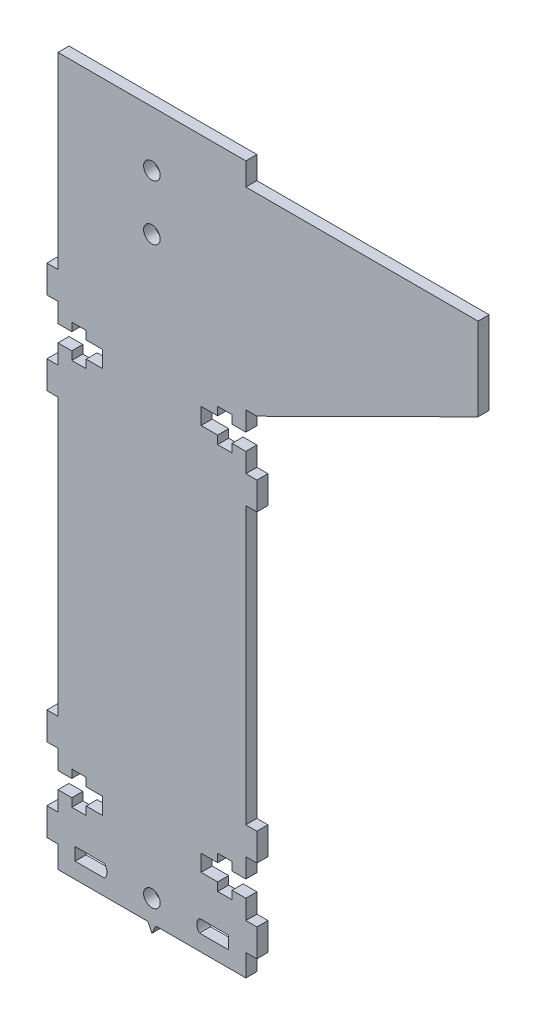
SolidWorks part; units mm, degrees
ref_plane "前视基准面" through (0, 0, 0) normal (0, 0, 1) x (1, 0, 0)
ref_plane "上视基准面" through (0, 0, 0) normal (0, 1, 0) x (1, 0, 0)
ref_plane "右视基准面" through (0, 0, 0) normal (1, 0, 0) x (0, 0, -1)
sketch "草图1" plane through (0, 0, 0) normal (0, 0, 1) x (1, 0, 0)
  line L35 (16.9939, 15.9) -> (16.9939, 20)
  line L36 (58.9939, 15.9) -> (16.9939, 15.9)
  line L37 (58.9939, 0.9) -> (58.9939, 15.9)
  line L40 (18.9939, -34) -> (16.9939, -34)
  line L41 (18.9939, -29) -> (16.9939, -29)
  line L42 (18.9939, -34) -> (18.9939, -29)
  line L47 (16.9939, -22.5) -> (16.9939, -19)
  line L64 (0, -108) -> (0, -109.5)
  line L77 (-13.9, -102.85) -> (-8.6, -102.85)
  line L78 (-13.9, -102.85) -> (-13.9, -105.15)
  line L79 (-13.9, -105.15) -> (-8.6, -105.15)
  line L94 (0, -109.5) -> (0.7212, -108)
  line L95 (0.7212, -108) -> (16.9939, -108)
  line L96 (-0.7212, -108) -> (-16.9939, -108)
  line L97 (0, -109.5) -> (-0.7212, -108)
  line L124 (16.9939, -25.5) -> (16.9939, -29)
  line L126 (14.4939, -25.5) -> (16.9939, -25.5)
  line L127 (14.4939, -21) -> (11.8939, -21)
  line L128 (11.8939, -21) -> (11.8939, -22.5)
  line L129 (11.8939, -22.5) -> (8.8939, -22.5)
  line L130 (11.8939, -25.5) -> (8.8939, -25.5)
  line L131 (11.8939, -27) -> (11.8939, -25.5)
  line L132 (14.4939, -27) -> (11.8939, -27)
  line L133 (16.9939, -22.5) -> (14.4939, -22.5)
  line L134 (14.4939, -22.5) -> (14.4939, -21)
  line L135 (8.8939, -22.5) -> (8.8939, -25.5)
  line L136 (14.4939, -25.5) -> (14.4939, -27)
  line L138 (-18.9939, -104) -> (-18.9939, -99)
  line L139 (-18.9939, -99) -> (-16.9939, -99)
  line L140 (-18.9939, -104) -> (-16.9939, -104)
  line L141 (-14.4939, -95.5) -> (-14.4939, -97)
  line L142 (-8.8939, -92.5) -> (-8.8939, -95.5)
  line L143 (-14.4939, -92.5) -> (-14.4939, -91)
  line L144 (-16.9939, -92.5) -> (-14.4939, -92.5)
  line L145 (-14.4939, -97) -> (-11.8939, -97)
  line L146 (-11.8939, -97) -> (-11.8939, -95.5)
  line L147 (-11.8939, -95.5) -> (-8.8939, -95.5)
  line L148 (-11.8939, -92.5) -> (-8.8939, -92.5)
  line L149 (-11.8939, -91) -> (-11.8939, -92.5)
  line L150 (-14.4939, -91) -> (-11.8939, -91)
  line L151 (-14.4939, -95.5) -> (-16.9939, -95.5)
  line L152 (-16.9939, -89) -> (-16.9939, -92.5)
  line L153 (-16.9939, -95.5) -> (-16.9939, -99)
  line L154 (-16.9939, -89) -> (-18.9939, -89)
  line L155 (-18.9939, -89) -> (-18.9939, -84)
  line L156 (-18.9939, -84) -> (-16.9939, -84)
  line L158 (-16.9939, -104) -> (-16.9939, -108)
  line L179 (-14.4939, -25.5) -> (-14.4939, -27)
  line L180 (-8.8939, -22.5) -> (-8.8939, -25.5)
  line L181 (-14.4939, -22.5) -> (-14.4939, -21)
  line L182 (-16.9939, -22.5) -> (-14.4939, -22.5)
  line L183 (-14.4939, -27) -> (-11.8939, -27)
  line L184 (-11.8939, -27) -> (-11.8939, -25.5)
  line L185 (-11.8939, -25.5) -> (-8.8939, -25.5)
  line L186 (-11.8939, -22.5) -> (-8.8939, -22.5)
  line L187 (-11.8939, -21) -> (-11.8939, -22.5)
  line L188 (-14.4939, -21) -> (-11.8939, -21)
  line L189 (-14.4939, -25.5) -> (-16.9939, -25.5)
  line L190 (-16.9939, -25.5) -> (-16.9939, -29)
  line L191 (-16.9939, -22.5) -> (-16.9939, -19)
  line L192 (-18.9939, -34) -> (-18.9939, -29)
  line L193 (-18.9939, -29) -> (-16.9939, -29)
  line L194 (-18.9939, -34) -> (-16.9939, -34)
  line L195 (-16.9939, -34) -> (-16.9939, -84)
  line L199 (-18.9939, -19) -> (-16.9939, -19)
  line L200 (-16.9939, 15.9) -> (-16.9939, 20)
  line L201 (-16.9939, 20) -> (16.9939, 20)
  line L207 (16.9939, -84) -> (16.9939, -34)
  line L210 (-18.9939, -19) -> (-18.9939, -14)
  line L211 (-18.9939, -14) -> (-16.9939, -14)
  line L212 (-16.9939, -14) -> (-16.9939, 15.9)
  line L213 (16.9939, -19) -> (18.9939, -19)
  line L222 (0, -104) -> (0, -98.3813) construction
  line L223 (16.9939, -104) -> (16.9939, -108)
  line L224 (18.9939, -84) -> (16.9939, -84)
  line L225 (18.9939, -89) -> (18.9939, -84)
  line L226 (16.9939, -89) -> (18.9939, -89)
  line L227 (16.9939, -95.5) -> (16.9939, -99)
  line L228 (16.9939, -89) -> (16.9939, -92.5)
  line L229 (14.4939, -95.5) -> (16.9939, -95.5)
  line L230 (14.4939, -91) -> (11.8939, -91)
  line L231 (11.8939, -91) -> (11.8939, -92.5)
  line L232 (11.8939, -92.5) -> (8.8939, -92.5)
  line L233 (11.8939, -95.5) -> (8.8939, -95.5)
  line L234 (11.8939, -97) -> (11.8939, -95.5)
  line L235 (14.4939, -97) -> (11.8939, -97)
  line L236 (16.9939, -92.5) -> (14.4939, -92.5)
  line L237 (14.4939, -92.5) -> (14.4939, -91)
  line L238 (8.8939, -92.5) -> (8.8939, -95.5)
  line L239 (14.4939, -95.5) -> (14.4939, -97)
  line L240 (18.9939, -104) -> (16.9939, -104)
  line L241 (18.9939, -99) -> (16.9939, -99)
  line L242 (18.9939, -104) -> (18.9939, -99)
  line L243 (13.9, -105.15) -> (8.6, -105.15)
  line L244 (13.9, -102.85) -> (13.9, -105.15)
  line L245 (13.9, -102.85) -> (8.6, -102.85)
  line L246 (18.9939, -19) -> (58.9939, 0.9)
  circle A4 centre (0, -104) radius 1.5
  circle A6 centre (0, 0) radius 1.5
  circle A7 centre (0, 10) radius 1.5
  arc A8 (-8.6, -102.85) -> (-8.6, -105.15) centre (-9.75, -104) cw
  arc A12 (8.6, -102.85) -> (8.6, -105.15) centre (9.75, -104) ccw
  point P108 (0, 0)
extrude "凸台-拉伸1" add sketch "草图1" along normal blind 2
sketch "草图7" plane through (-16.9939, 0, 0) normal (-1, 0, 0) x (0, 0, 1)
  line L0 (1, -92.5) -> (1, -95.5)
  line L1 (2, -92.5) -> (0, -92.5) construction
  line L2 (2, -95.5) -> (0, -95.5) construction
  circle A0 centre (1, -94) radius 1.5
sketch "草图8" plane through (16.9939, 0, 0) normal (1, 0, 0) x (0, 0, -1)
  line L0 (-1, -22.5) -> (-1, -25.5) construction
  line L1 (-2, -22.5) -> (0, -22.5) construction
  line L2 (-2, -25.5) -> (0, -25.5) construction
  circle A0 centre (-1, -24) radius 1.5
sketch "草图6" plane through (-16.9939, 0, 0) normal (-1, 0, 0) x (0, 0, 1)
  line L0 (1, -92.5) -> (1, -95.5)
  line L1 (2, -92.5) -> (0, -92.5) construction
  line L2 (2, -95.5) -> (0, -95.5) construction
  circle A0 centre (1, -94) radius 1.5
